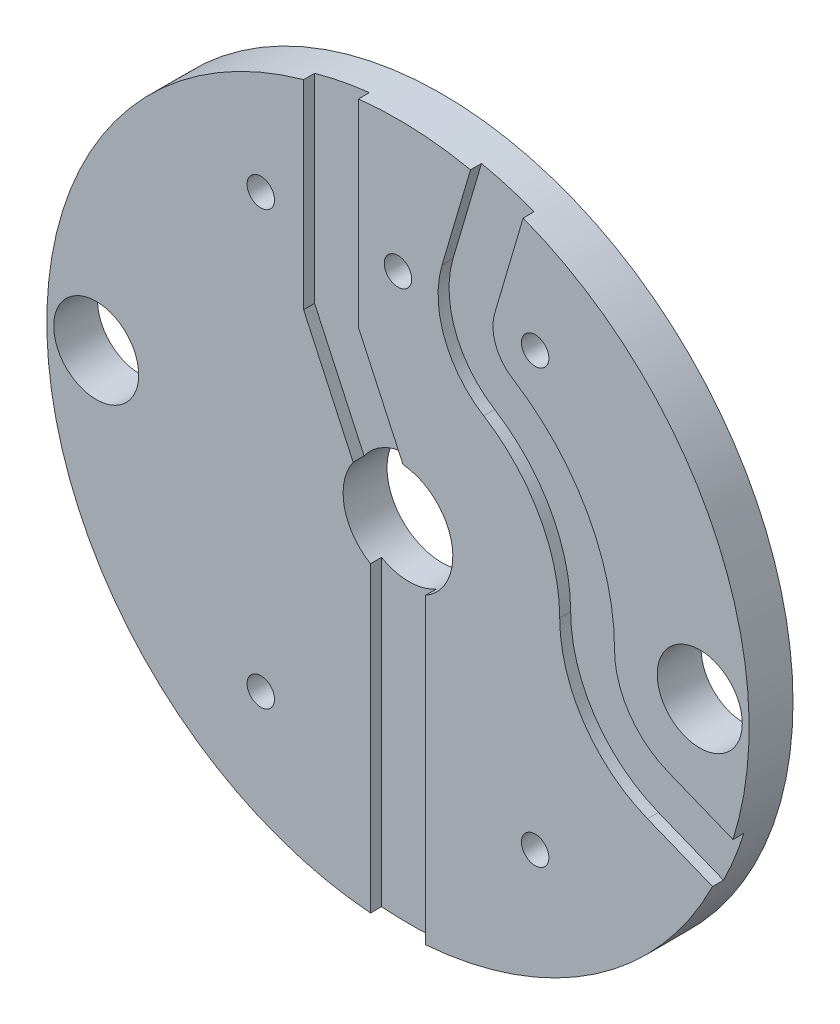
SolidWorks part; units mm, degrees
ref_plane "Plan de face" through (0, 0, 0) normal (0, 0, 1) x (1, 0, 0)
ref_plane "Plan de dessus" through (0, 0, 0) normal (0, 1, 0) x (1, 0, 0)
ref_plane "Plan de droite" through (0, 0, 0) normal (1, 0, 0) x (0, 0, -1)
sketch "Esquisse1" plane through (0, 0, 0) normal (0, 0, 1) x (1, 0, 0)
  circle A0 centre (0, 0) radius 2
  circle A1 centre (0, 0) radius 12.8
  circle A2 centre (-11, 0) radius 1.55
  circle A3 centre (11, 0) radius 1.55
  dimension "D1" = 11
  dimension "D2" = 11
extrude "Boss.-Extru.1" add sketch "Esquisse1" along normal blind 1.6
sketch "Esquisse2" plane through (0, 0, 1.6) normal (0, 0, 1) x (1, 0, 0)
  line L0 (-0.11, -7.7652) -> (7.7721, -7.7652) construction
  line L1 (0, 7.999) -> (11.3555, 7.999) construction
  circle A0 centre (5, -7.7652) radius 0.5
  circle A1 centre (-5, -7.7652) radius 0.5
  circle A2 centre (0, 7.999) radius 0.5
  circle A3 centre (5, 7.999) radius 0.5
  circle A4 centre (-5, 7.999) radius 0.5
  dimension "D1" = 5
  dimension "D3" = 5
  dimension "D2" = 5
  dimension "D4" = 5
extrude "Enlèv. mat.-Extru.1" cut sketch "Esquisse2" against normal through all
sketch "Esquisse3" plane through (0, 0, 1.6) normal (0, 0, 1) x (1, 0, 0)
  line L0 (0, 0) -> (-3.6738, 13.6099)
  line L1 (0, -3.7239) -> (0, -13.2091)
  line L2 (1.9371, 13.2425) -> (9.0844, -9.6021)
sketch "Esquisse4" plane through (0, 0, 1.6) normal (0, 0, 1) x (1, 0, 0)
  line L0 (2.8499, 13.2238) -> (4.7685, 12.6591)
  line L1 (13.1732, -4.2207) -> (12.4268, -6.0762)
  line L2 (1.606, 8.9979) -> (2.8499, 13.2238)
  line L3 (9.095, -4.7361) -> (12.4268, -6.0762)
  line L4 (3.5246, 8.4332) -> (4.7685, 12.6591)
  line L5 (9.8414, -2.8806) -> (13.1732, -4.2207)
  line L6 (-3.4398, 13.2238) -> (-1.4398, 13.2238)
  line L7 (-1, -13.7727) -> (1, -13.7727)
  line L9 (-3.4398, 13.2238) -> (-3.4398, 5.0667)
  line L10 (-3.4398, 5.0667) -> (-1, -0.2196)
  line L11 (-1, -0.2196) -> (-1, -13.7727)
  line L12 (-1.4398, 13.2238) -> (-1.4398, 5.5059)
  line L13 (-1.4398, 5.5059) -> (1, 0.2196)
  line L14 (1, 0.2196) -> (1, -13.7727)
  arc A3 (1.606, 8.9979) -> (3.1247, 4.9989) centre (5, 7.999) ccw
  arc A4 (5.8952, 0) -> (3.1247, 4.9989) centre (0, 0) ccw
  arc A5 (5.8952, 0) -> (9.095, -4.7361) centre (11, 0) ccw
  arc A6 (3.5246, 8.4332) -> (4.1848, 6.6948) centre (5, 7.999) ccw
  arc A7 (7.8952, 0) -> (4.1848, 6.6948) centre (0, 0) ccw
  arc A8 (7.8952, 0) -> (9.8414, -2.8806) centre (11, 0) ccw
extrude "Enlèv. mat.-Extru.2" cut sketch "Esquisse4" against normal blind 0.4
